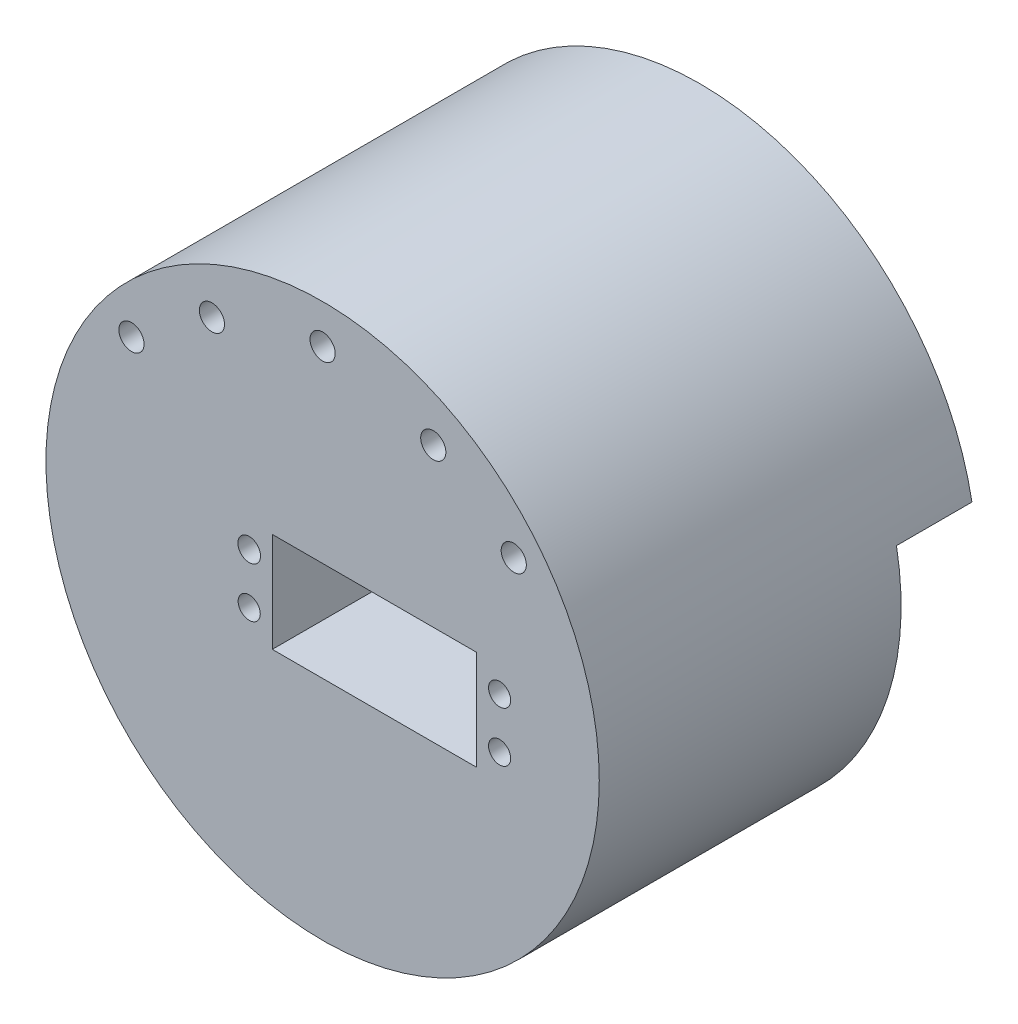
SolidWorks part; units mm, degrees
ref_plane "Front Plane" through (0, 0, 0) normal (0, 0, 1) x (1, 0, 0)
ref_plane "Top Plane" through (0, 0, 0) normal (0, 1, 0) x (1, 0, 0)
ref_plane "Right Plane" through (0, 0, 0) normal (1, 0, 0) x (0, 0, -1)
sketch "Sketch1" plane through (0, 0, 0) normal (0, 0, 1) x (1, 0, 0)
  line L0 (-54.0833, 10) -> (-38, 10)
  line L1 (-38, -20) -> (-38, 20) construction
  line L2 (-40, 10) -> (-53, 10) construction
  line L3 (-40, 10) -> (-53, 10)
  line L4 (-38, 10) -> (-38, 20)
  line L5 (38, 20) -> (38, -20) construction
  line L6 (38, 20) -> (38, 10)
  line L7 (0, 0) -> (0, 30.5038) construction
  line L8 (54.0833, 10) -> (38, 10)
  arc A0 (55, 0) -> (-55, 0) centre (0, 0) ccw construction
  arc A1 (54.0833, 10) -> (-54.0833, 10) centre (0, 0) ccw
  parabola Q0 (-38, 20) -> (0, 39.5) focus (-30.2821, 8.8103) apex (-41.8802, 12.829) construction
  parabola Q1 (-38, 20) -> (0, 39.5) focus (-30.2821, 8.8103) apex (-41.8802, 12.829)
  parabola Q2 (0, 39.5) -> (38, 20) focus (30.2821, 8.8103) apex (41.8802, 12.829) construction
  parabola Q3 (0, 39.5) -> (38, 20) focus (30.2821, 8.8103) apex (41.8802, 12.829)
extrude "Boss-Extrude1" add sketch "Sketch1" along normal blind 35 contours Q1 Q3 L6 L8 A1 L0 L4
sketch "Sketch2" plane through (0, 0, 35) normal (0, 0, 1) x (1, 0, 0)
  circle A0 centre (0, 0) radius 39.161
  circle A1 centre (0, 0) radius 55
extrude "Boss-Extrude2" add sketch "Sketch2" against normal blind 40 from offset 20
sketch "Sketch4" plane through (0, 0, 55) normal (0, 0, 1) x (1, 0, 0)
  circle A0 centre (0, 0) radius 55
extrude "Boss-Extrude3" add sketch "Sketch4" along normal blind 20
sketch "Sketch5" plane through (0, 0, 75) normal (0, 0, 1) x (1, 0, 0)
  circle A0 centre (0, 0) radius 3
  dimension "D1" = 6
extrude "Cut-Extrude1" cut sketch "Sketch5" against normal blind 20
sketch "Sketch6" plane through (0, 0, 75) normal (0, 0, 1) x (1, 0, 0)
  circle A0 centre (-38, 29.8809) radius 2.5
  circle A1 centre (-22, 41.2665) radius 2.5
  circle A2 centre (0, 47.25) radius 2.5
  circle A3 centre (22, 41.2665) radius 2.5
  circle A4 centre (38, 29.8809) radius 2.5
  dimension "D1" = 5
extrude "Cut-Extrude3" cut sketch "Sketch6" against normal through all
sketch "Sketch8" plane through (0, 0, 75) normal (0, 0, 1) x (1, 0, 0)
  line L1 (-10, 9.9) -> (30.5963, 9.9)
  line L2 (-10, 9.9) -> (-10, -9.8959)
  line L3 (-10, -9.8959) -> (30.5963, -9.8959)
  line L4 (30.5963, 9.9) -> (30.5963, -9.8959)
  circle A0 centre (-14.5896, 5) radius 2.25
  circle A1 centre (-14.5896, -5) radius 2.2
  circle A2 centre (35.1896, 5) radius 2.2
  circle A3 centre (35.1896, -5) radius 2.2
  dimension "D1" = 4.5
extrude "Cut-Extrude5" cut sketch "Sketch8" against normal blind 30
